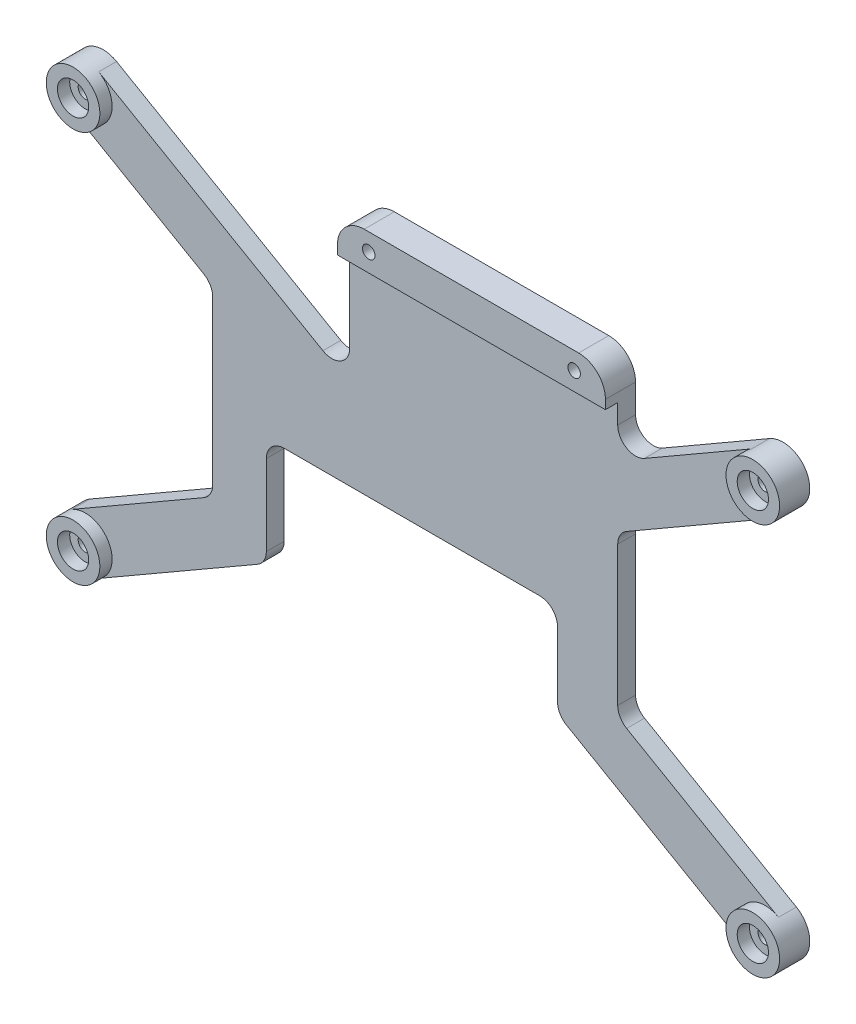
SolidWorks part; units mm, degrees
ref_plane "Front Plane" through (0, 0, 0) normal (0, 0, 1) x (1, 0, 0)
ref_plane "Top Plane" through (0, 0, 0) normal (0, 1, 0) x (1, 0, 0)
ref_plane "Right Plane" through (0, 0, 0) normal (1, 0, 0) x (0, 0, -1)
sketch "Sketch1" plane through (0, 0, 0) normal (0, 0, 1) x (1, 0, 0)
  line L0 (49.3077, 34.8539) -> (125.4061, 78.7705) construction
  line L1 (49.3077, 78.7705) -> (125.4061, 34.8539) construction
  line L2 (47.8081, 76.1722) -> (63.5683, 67.077)
  line L3 (50.8072, 81.3689) -> (78.9052, 65.1534)
  line L4 (126.9056, 76.1722) -> (108.9052, 65.7841)
  line L5 (47.8081, 37.4523) -> (63.5683, 46.5475)
  line L6 (102.1683, 44.8008) -> (123.9065, 32.2556)
  line L7 (69.5683, 43.0827) -> (50.8072, 32.2556)
  line L9 (108.9052, 72.7116) -> (123.9065, 81.3689)
  line L10 (46.2684, 82.7502) -> (134.7444, 82.7502) construction
  line L13 (78.9052, 82.3502) -> (108.9052, 82.3502)
  line L14 (108.9052, 47.8403) -> (108.9052, 65.7841)
  line L15 (78.9052, 65.1534) -> (78.9052, 82.3502)
  line L16 (69.5683, 43.0827) -> (69.5683, 55.2558)
  line L18 (63.5683, 46.5475) -> (63.5683, 67.077)
  line L19 (108.9052, 72.7116) -> (108.9052, 82.3502)
  line L20 (45.4684, 84.0502) -> (142.3421, 84.0502) construction
  line L23 (102.1683, 44.8008) -> (102.1683, 55.2558)
  line L24 (102.1683, 55.2558) -> (69.5683, 55.2558)
  line L25 (108.9052, 47.8403) -> (126.9056, 37.4523)
  line L27 (71.5683, 53.2558) -> (71.5683, 49.7358) construction
  line L28 (93.9052, 60.5913) -> (93.9052, 84.0502) construction
  line L29 (100.1683, 53.2558) -> (100.1683, 52.2558) construction
  line L31 (72.3183, 53.2558) -> (75.9483, 53.2558) construction
  arc A0 (50.8072, 81.3689) -> (47.8081, 76.1722) centre (49.3077, 78.7705) ccw
  arc A1 (47.8081, 37.4523) -> (50.8072, 32.2556) centre (49.3077, 34.8539) ccw
  arc A2 (123.9065, 32.2556) -> (126.9056, 37.4523) centre (125.4061, 34.8539) ccw
  arc A3 (126.9056, 76.1722) -> (123.9065, 81.3689) centre (125.4061, 78.7705) ccw
  circle A5 centre (125.4061, 78.7705) radius 1.4 construction
  circle A6 centre (49.3077, 34.8539) radius 1.4 construction
  circle A7 centre (49.3077, 78.7705) radius 1.4 construction
  circle A8 centre (125.4061, 34.8539) radius 1.4 construction
  point P52 (93.9052, 82.3502)
  dimension "D1" = 6
  dimension "D2" = 0.4
  dimension "D3" = 6
  dimension "D4" = 2
  dimension "D5" = 2
  dimension "D6" = 2
  dimension "D7" = 30
extrude "Boss-Extrude1" add sketch "Sketch1" along normal blind 2
sketch "Sketch2" plane through (0, 0, 2) normal (0, 0, 1) x (1, 0, 0)
  line L0 (49.3077, 78.7705) -> (49.3077, 34.8539) construction
  line L1 (125.4061, 34.8539) -> (125.4061, 78.7705) construction
  line L2 (49.3077, 56.8122) -> (125.4061, 56.8122) construction
  line L3 (87.3569, 56.8122) -> (87.3569, 84.0502) construction
  line L4 (45.4684, 84.0502) -> (142.3421, 84.0502) construction
  circle A0 centre (49.3077, 78.7705) radius 3
  circle A1 centre (49.3077, 78.7705) radius 1.75
  circle A3 centre (49.3077, 34.8539) radius 1.75
  circle A4 centre (49.3077, 34.8539) radius 3
  circle A5 centre (125.4061, 34.8539) radius 3
  circle A6 centre (125.4061, 34.8539) radius 1.75
  circle A7 centre (125.4061, 78.7705) radius 1.75
  circle A8 centre (125.4061, 78.7705) radius 3
  dimension "D1" = 3.5
extrude "Boss-Extrude2" add sketch "Sketch2" along normal up to surface (1.3744 mm away)
fillet "Fillet1" radius 2 10 edges at (63.5683, 46.5475, 1) (63.5683, 67.077, 1) (78.9052, 65.1534, 1) (108.9052, 72.7116, 1) (108.9052, 65.7841, 1) (108.9052, 47.8403, 1) (102.1683, 44.8008, 1) (102.1683, 55.2558, 1) (69.5683, 43.0827, 1) (69.5683, 55.2558, 1)
sketch "Sketch3" plane through (0, 0, 0) normal (0, 0, -1) x (-1, 0, 0)
  circle A0 centre (-125.4061, 78.7705) radius 0.8
  circle A1 centre (-125.4061, 34.8539) radius 0.8
  circle A2 centre (-49.3077, 34.8539) radius 0.8
  circle A3 centre (-49.3077, 78.7705) radius 0.8
  dimension "D1" = 1.6
extrude "Cut-Extrude1" cut sketch "Sketch3" against normal up to next
sketch "Sketch6" plane through (0, 0, 2) normal (0, 0, 1) x (1, 0, 0)
  line L0 (108.9052, 76.175) -> (108.9052, 82.3502) construction
  line L1 (78.9052, 82.3502) -> (108.9052, 82.3502)
  line L2 (78.9052, 82.3502) -> (78.9052, 78.3502)
  line L3 (78.9052, 78.3502) -> (108.9052, 78.3502)
  line L4 (108.9052, 82.3502) -> (108.9052, 78.3502)
  dimension "D1" = 4
extrude "Boss-Extrude4" add sketch "Sketch6" along normal up to surface (1.3744 mm away)
sketch "Sketch7" plane through (0, 0, 0) normal (0, 0, -1) x (-1, 0, 0)
  line L0 (-93.9052, 82.3502) -> (-93.9052, 55.2558) construction
  line L1 (-108.9052, 82.3502) -> (-78.9052, 82.3502) construction
  line L2 (-71.5683, 55.2558) -> (-100.1683, 55.2558) construction
  circle A0 centre (-105.4052, 80.3943) radius 0.7
  circle A1 centre (-105.4052, 80.3943) radius 1.5 construction
  circle A2 centre (-82.4052, 80.3943) radius 0.7
  dimension "D1" = 1.4
extrude "Cut-Extrude3" cut sketch "Sketch7" against normal through all
fillet "Fillet2" radius 3 2 edges at (78.9052, 82.3502, 1.6872) (108.9052, 82.3502, 1.6872)
